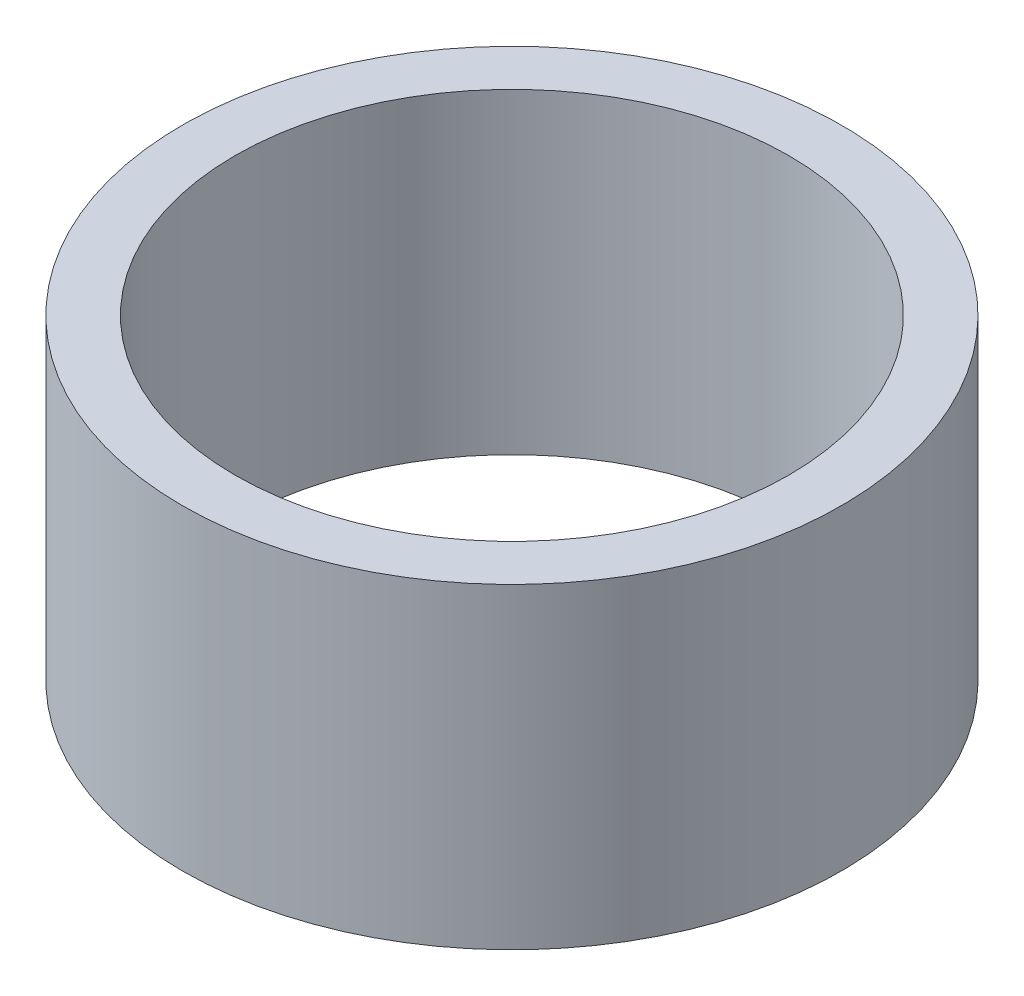
SolidWorks part; units mm, degrees
material "PETG"
ref_plane "Спереди" through (0, 0, 0) normal (0, 0, 1) x (1, 0, 0)
ref_plane "Сверху" through (0, 0, 0) normal (0, 1, 0) x (1, 0, 0)
ref_plane "Справа" through (0, 0, 0) normal (1, 0, 0) x (0, 0, -1)
sketch "Эскиз1" plane through (0, 0, 0) normal (0, 1, 0) x (1, 0, 0)
  circle A0 centre (0, 0) radius 5.25
  circle A1 centre (0, 0) radius 6.25
  dimension "D1" = 10.5
  dimension "D2" = 12.5
extrude "Бобышка-Вытянуть1" add sketch "Эскиз1" along normal blind 6
